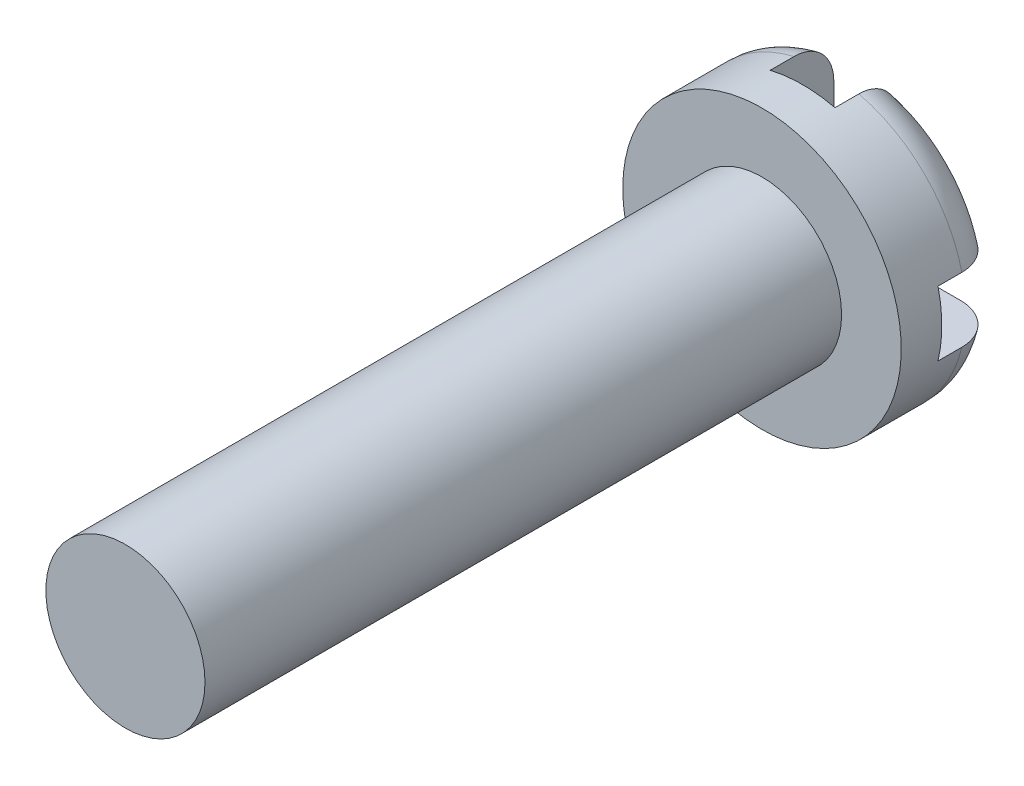
SolidWorks part; units mm, degrees
ref_plane "前视基准面" through (0, 0, 0) normal (0, 0, 1) x (1, 0, 0)
ref_plane "上视基准面" through (0, 0, 0) normal (0, 1, 0) x (1, 0, 0)
ref_plane "右视基准面" through (0, 0, 0) normal (1, 0, 0) x (0, 0, -1)
sketch "草图1" plane through (0, 0, 0) normal (0, 0, 1) x (1, 0, 0)
  circle A0 centre (0, 0) radius 1
extrude "凸台-拉伸1" add sketch "草图1" along normal blind 8
sketch "草图2" plane through (0, 0, 0) normal (0, 0, -1) x (-1, 0, 0)
  circle A0 centre (0, 0) radius 1.75
  dimension "D1" = 3.5
extrude "凸台-拉伸2" add sketch "草图2" along normal blind 1.31
fillet "圆角1" radius 0.5 1 edges at (-1.75, 0, -1.31)
sketch "草图3" plane through (0, 0, -1.31) normal (0, 0, -1) x (-1, 0, 0)
  line L0 (-0.7071, 0.7071) -> (-0.7071, 6.0064) construction
  line L1 (1, -1) -> (-1, -1) construction
  line L2 (1, -1) -> (1, 1) construction
  line L3 (1, 1) -> (-1, 1) construction
  line L4 (-1, -1) -> (-1, 1) construction
  line L5 (1, -1) -> (-1, 1) construction
  line L6 (1, 1) -> (-1, -1) construction
  line L7 (0.7071, 0.7071) -> (0.7071, 6.0064) construction
  line L8 (0.7071, 6.0064) -> (-0.7071, 6.0064) construction
  line L9 (0.7071, 0.7071) -> (6.0064, 0.7071) construction
  line L10 (0.7071, -0.7071) -> (6.0064, -0.7071) construction
  line L11 (6.0064, -0.7071) -> (6.0064, 0.7071) construction
  line L12 (0.7071, -0.7071) -> (0.7071, -6.0064) construction
  line L13 (-0.7071, -0.7071) -> (-0.7071, -6.0064) construction
  line L14 (-0.7071, -6.0064) -> (0.7071, -6.0064) construction
  line L15 (-0.7071, -0.7071) -> (-6.0064, -0.7071) construction
  line L16 (-0.7071, 0.7071) -> (-6.0064, 0.7071) construction
  line L17 (-6.0064, 0.7071) -> (-6.0064, -0.7071) construction
  line L18 (0.4071, 0.4071) -> (0.4071, 5.7064)
  line L19 (0.4071, 5.7064) -> (-0.4071, 5.7064)
  line L20 (-0.4071, 0.4071) -> (-0.4071, 5.7064)
  line L21 (-0.4071, 0.4071) -> (-5.7064, 0.4071)
  line L22 (-5.7064, 0.4071) -> (-5.7064, -0.4071)
  line L23 (-0.4071, -0.4071) -> (-5.7064, -0.4071)
  line L24 (-0.4071, -0.4071) -> (-0.4071, -5.7064)
  line L25 (-0.4071, -5.7064) -> (0.4071, -5.7064)
  line L26 (0.4071, -0.4071) -> (0.4071, -5.7064)
  line L27 (0.4071, -0.4071) -> (5.7064, -0.4071)
  line L28 (5.7064, -0.4071) -> (5.7064, 0.4071)
  line L29 (0.4071, 0.4071) -> (5.7064, 0.4071)
  circle A0 centre (0, 0) radius 1 construction
  dimension "D1" = 4
  dimension "D2" = 0.3
extrude "切除-拉伸1" cut sketch "草图3" against normal blind 0.8
